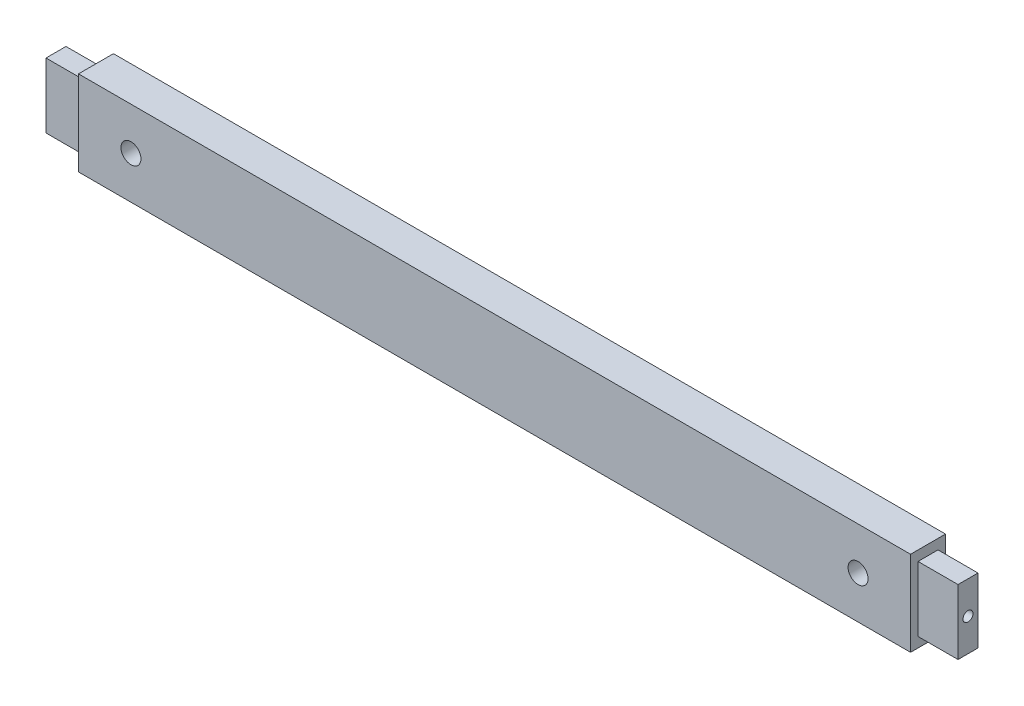
SolidWorks part; units mm, degrees
ref_plane "Front Plane" through (0, 0, 0) normal (0, 0, 1) x (1, 0, 0)
ref_plane "Top Plane" through (0, 0, 0) normal (0, 1, 0) x (1, 0, 0)
ref_plane "Right Plane" through (0, 0, 0) normal (1, 0, 0) x (0, 0, -1)
sketch "Sketch2" plane through (0, 0, 0) normal (0, 0, 1) x (1, 0, 0)
  line L1 (528.6375, 53.975) -> (-528.6375, 53.975)
  line L2 (528.6375, 53.975) -> (528.6375, -53.975)
  line L3 (528.6375, -53.975) -> (-528.6375, -53.975)
  line L4 (-528.6375, 53.975) -> (-528.6375, -53.975)
  line L5 (528.6375, 53.975) -> (-528.6375, -53.975) construction
  line L6 (528.6375, -53.975) -> (-528.6375, 53.975) construction
  point P0 (0, 0)
  dimension "D1" = 107.95
  dimension "D2" = 1057.275
extrude "Boss-Extrude1" add sketch "Sketch2" along normal mid plane 44.45
sketch "Sketch3" plane through (528.6375, 0, 0) normal (1, 0, 0) x (0, 0, -1)
  line L1 (12.7, 41.275) -> (-12.7, 41.275)
  line L2 (12.7, 41.275) -> (12.7, -41.275)
  line L3 (12.7, -41.275) -> (-12.7, -41.275)
  line L4 (-12.7, 41.275) -> (-12.7, -41.275)
  line L5 (12.7, 41.275) -> (-12.7, -41.275) construction
  line L6 (12.7, -41.275) -> (-12.7, 41.275) construction
  point P0 (0, 0)
  dimension "D1" = 82.55
  dimension "D2" = 25.4
extrude "Boss-Extrude2" add sketch "Sketch3" along normal blind 50.8
sketch "Sketch4" plane through (579.4375, 0, 0) normal (1, 0, 0) x (0, 0, -1)
  circle A0 centre (0, 0) radius 6.35
  dimension "D1" = 12.7
extrude "Cut-Extrude1" cut sketch "Sketch4" against normal blind 117.475
mirror "Mirror1" about plane through (0, 0, 0) normal (1, 0, 0) of "Boss-Extrude2", "Cut-Extrude1"
sketch "Sketch5" plane through (528.6375, 0, 0) normal (1, 0, 0) x (0, 0, -1)
  line L0 (22.225, -53.975) -> (22.225, 53.975) construction
  line L1 (22.225, 28.575) -> (19.05, 28.575)
  line L2 (22.225, 28.575) -> (22.225, 19.05)
  line L3 (22.225, 19.05) -> (19.05, 19.05)
  line L4 (19.05, 28.575) -> (19.05, 19.05)
  line L5 (-22.225, -53.975) -> (22.225, -53.975) construction
  dimension "D1" = 9.525
  dimension "D2" = 3.175
  dimension "D3" = 73.025
extrude "Cut-Extrude2" cut sketch "Sketch5" against normal through all
sketch "Sketch6" plane through (0, 0, -22.225) normal (0, 0, -1) x (-1, 0, 0)
  line L0 (-15.3051, 0) -> (-444.846, 0) construction
  line L1 (528.6375, -41.275) -> (528.6375, 41.275) construction
  line L2 (-528.6375, -41.275) -> (-528.6375, 41.275) construction
  circle A0 centre (461.9625, 0) radius 12.7
  circle A1 centre (-461.9625, 0) radius 12.7
  dimension "D1" = 25.4
  dimension "D2" = 66.675
  dimension "D3" = 66.675
extrude "Cut-Extrude3" cut sketch "Sketch6" against normal through all
